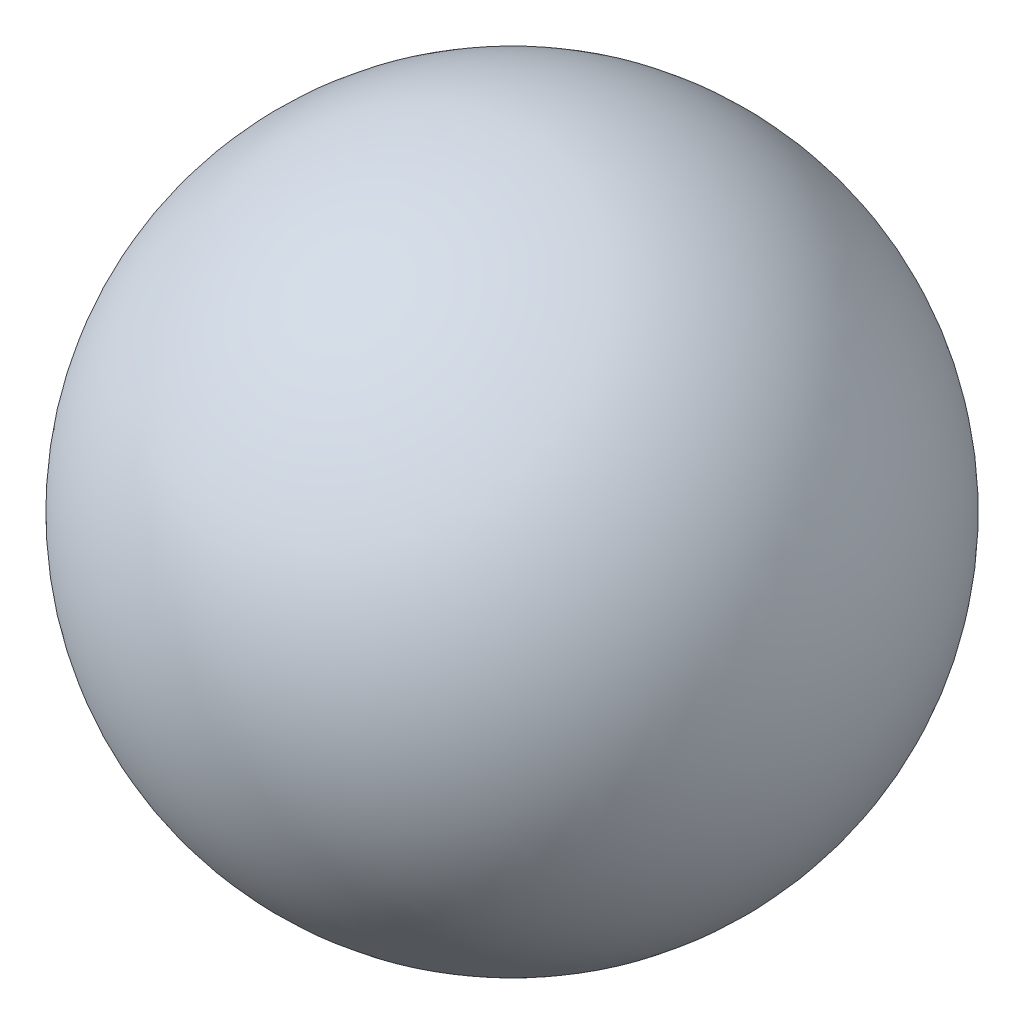
SolidWorks part; units mm, degrees
ref_plane "Front Plane" through (0, 0, 0) normal (0, 0, 1) x (1, 0, 0)
ref_plane "Top Plane" through (0, 0, 0) normal (0, 1, 0) x (1, 0, 0)
ref_plane "Right Plane" through (0, 0, 0) normal (1, 0, 0) x (0, 0, -1)
sketch "Sketch1" plane through (0, 0, 0) normal (0, 0, 1) x (1, 0, 0)
  line L0 (0, 105.0842) -> (0, -101.9811) construction
  line L1 (0, 21.5) -> (0, 16.75)
  line L2 (0, -16.75) -> (0, -21.5)
  arc A0 (0, 21.5) -> (0, -21.5) centre (0, 0) ccw
  arc A1 (0, 16.75) -> (0, -16.75) centre (0, 0) ccw
  dimension "D1" = 21.5
  dimension "D2" = 4.75
revolve "Revolve1" add sketch "Sketch1" angle 360 about L0
